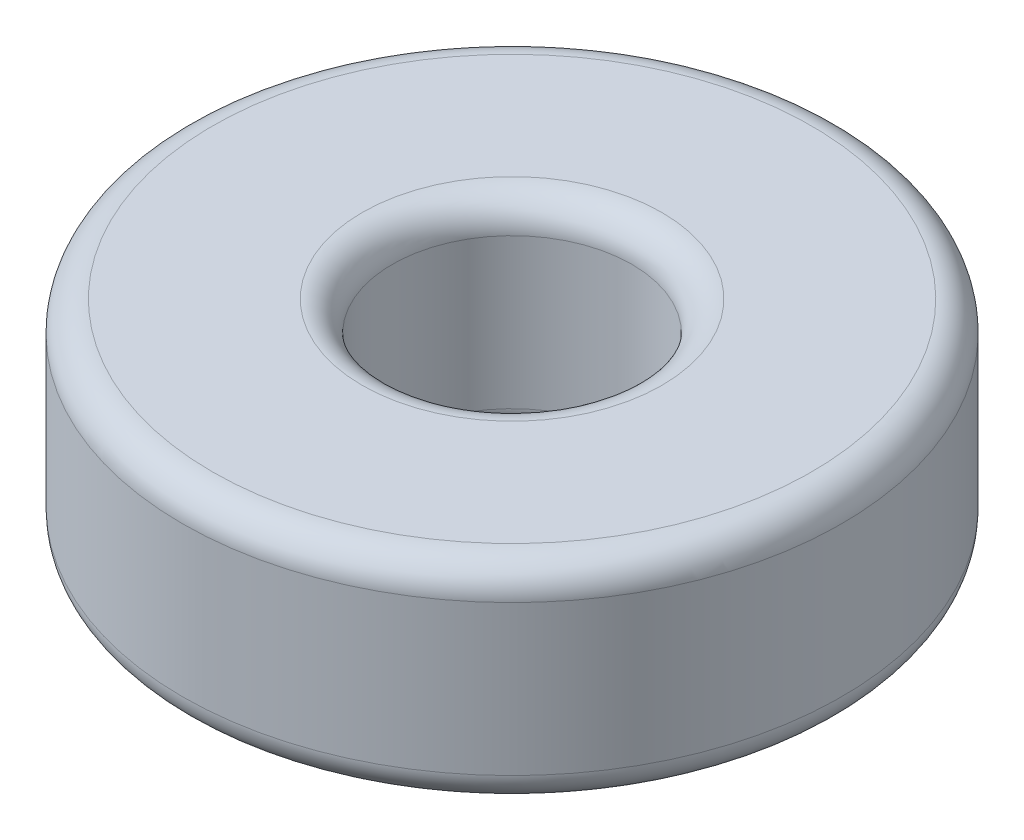
SolidWorks part; units mm, degrees
ref_plane "Front Plane" through (0, 0, 0) normal (0, 0, 1) x (1, 0, 0)
ref_plane "Top Plane" through (0, 0, 0) normal (0, 1, 0) x (1, 0, 0)
ref_plane "Right Plane" through (0, 0, 0) normal (1, 0, 0) x (0, 0, -1)
sketch "Sketch1" plane through (0, 0, 0) normal (0, 1, 0) x (1, 0, 0)
  circle A0 centre (0, 0) radius 11
  circle A1 centre (0, 0) radius 4
  dimension "D1" = 22
  dimension "D2" = 8
extrude "Boss-Extrude1" add sketch "Sketch1" along normal blind 7 contours A0 | A1
fillet "Fillet2" radius 1 4 edges at (0, 0, 4) (0, 0, 11) (0, 7, 4) (0, 7, 11)
